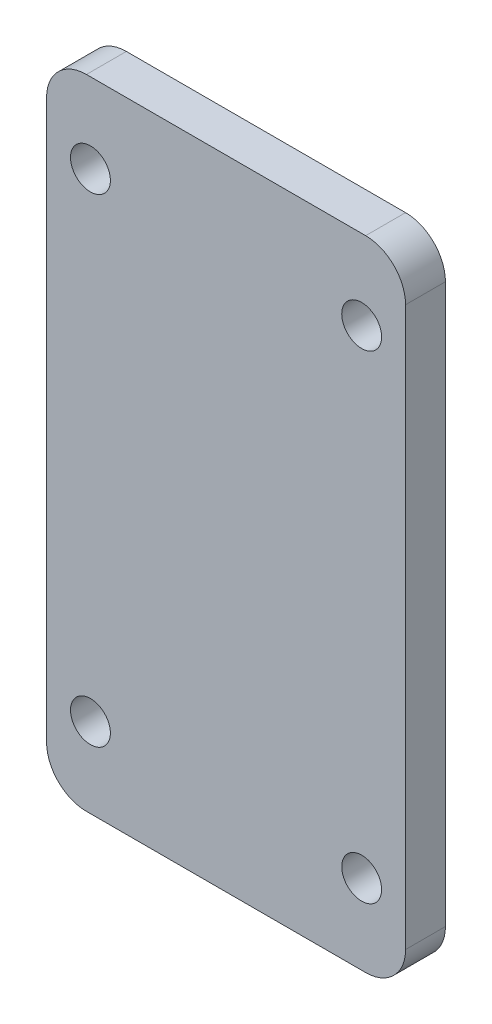
SolidWorks part; units mm, degrees
ref_plane "Plan de face" through (0, 0, 0) normal (0, 0, 1) x (1, 0, 0)
ref_plane "Plan de dessus" through (0, 0, 0) normal (0, 1, 0) x (1, 0, 0)
ref_plane "Plan de droite" through (0, 0, 0) normal (1, 0, 0) x (0, 0, -1)
sketch "Esquisse1" plane through (0, 0, 0) normal (0, 0, 1) x (1, 0, 0)
  line L0 (-22.5, 0) -> (22.5, 0) construction
  line L1 (-22.5, 40) -> (22.5, 40)
  line L2 (-22.5, 40) -> (-22.5, -40)
  line L3 (-22.5, -40) -> (22.5, -40)
  line L4 (22.5, 40) -> (22.5, -40)
  line L5 (-22.5, 40) -> (22.5, -40) construction
  line L6 (-22.5, -40) -> (22.5, 40) construction
  line L7 (0, -40) -> (0, 40) construction
  line L8 (-17, 40) -> (-17, -40) construction
  circle A0 centre (-17, 30) radius 2.5
  circle A1 centre (-17, -30) radius 2.5
  circle A2 centre (17, -30) radius 2.5
  circle A3 centre (17, 30) radius 2.5
  point P0 (0, 0)
  dimension "D4" = 5
  dimension "D1" = 45
  dimension "D2" = 80
  dimension "D3" = 17
  dimension "D5" = 10
extrude "Boss.-Extru.1" add sketch "Esquisse1" along normal blind 5
fillet "Congé1" radius 5 4 edges at (22.5, -40, 2.5) (-22.5, -40, 2.5) (22.5, 40, 2.5) (-22.5, 40, 2.5)
